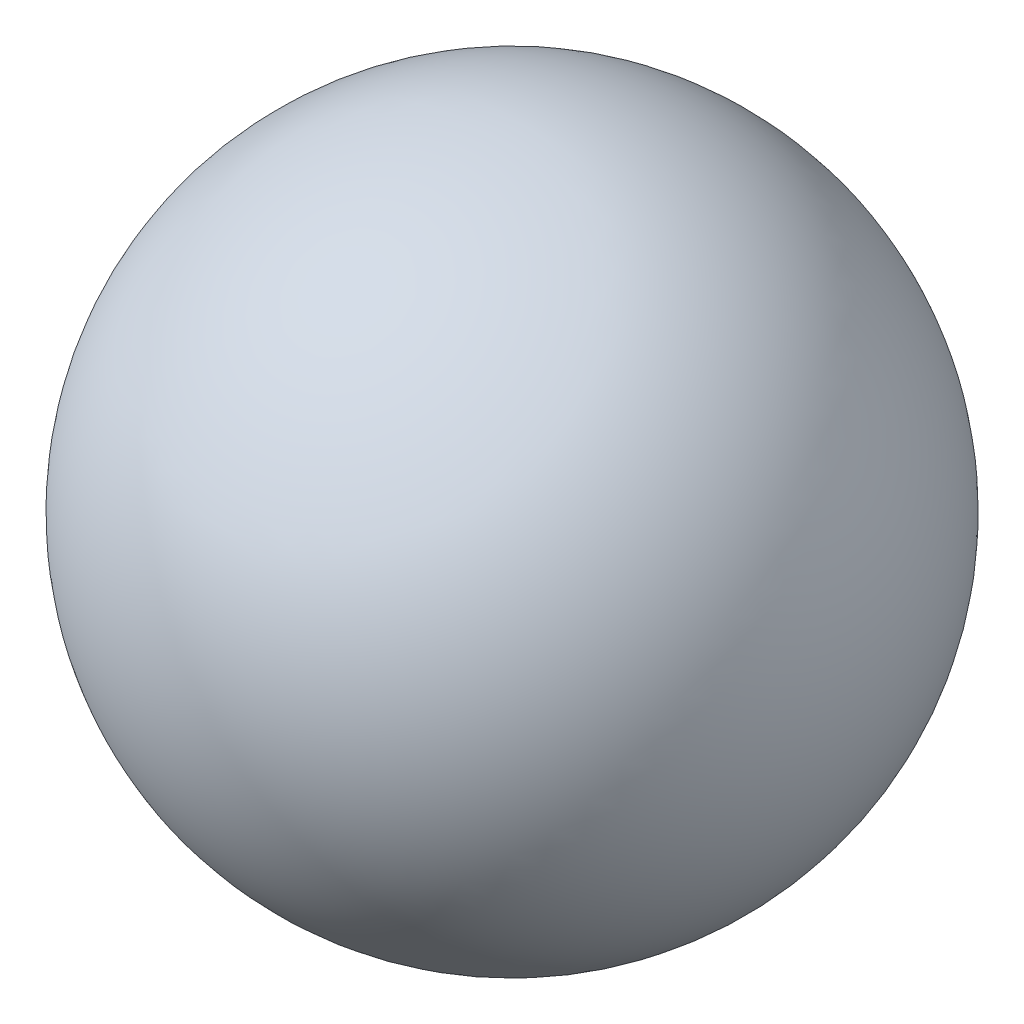
SolidWorks part; units mm, degrees
ref_plane "Plan de face" through (0, 0, 0) normal (0, 0, 1) x (1, 0, 0)
ref_plane "Plan de dessus" through (0, 0, 0) normal (0, 1, 0) x (1, 0, 0)
ref_plane "Plan de droite" through (0, 0, 0) normal (1, 0, 0) x (0, 0, -1)
sketch "Esquisse1" plane through (0, 0, 0) normal (0, 1, 0) x (1, 0, 0)
  line L0 (0, 32) -> (0, -32)
  line L1 (0, 32) -> (0, -32) construction
  arc A0 (0, -32) -> (0, 32) centre (0, 0) ccw
revolve "Révolution1" add sketch "Esquisse1" angle 360 about L1
